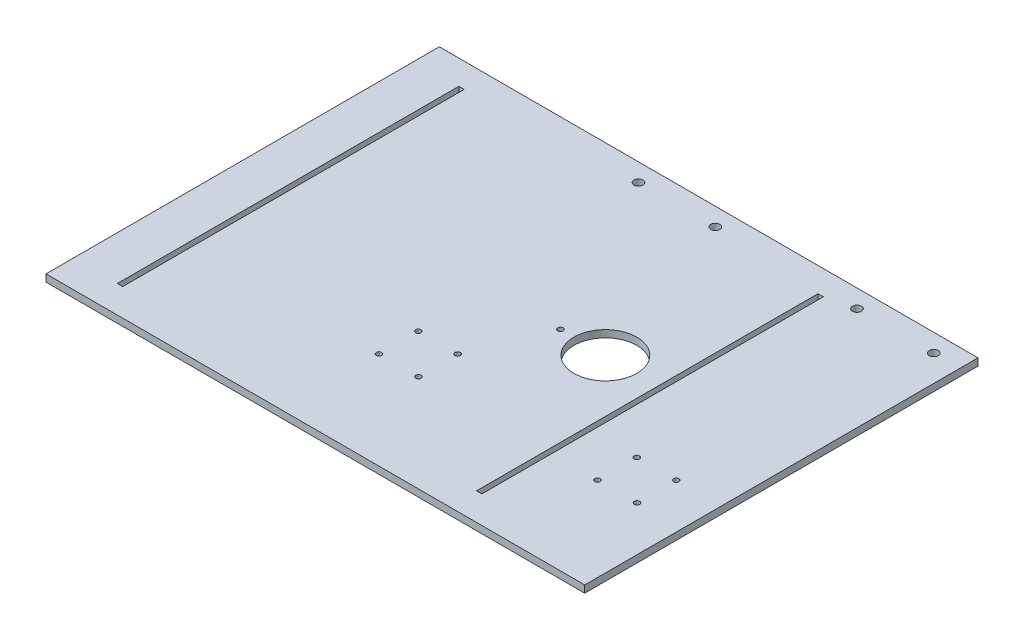
SolidWorks part; units mm, degrees
ref_plane "Front Plane" through (0, 0, 0) normal (0, 0, 1) x (1, 0, 0)
ref_plane "Top Plane" through (0, 0, 0) normal (0, 1, 0) x (1, 0, 0)
ref_plane "Right Plane" through (0, 0, 0) normal (1, 0, 0) x (0, 0, -1)
sketch "Sketch1" plane through (0, 0, 0) normal (0, 1, 0) x (1, 0, 0)
  line L0 (-125.5, 95.8859) -> (-125.5, -94.2851)
  line L1 (-150, -109.5) -> (150, -109.5)
  line L2 (-150, -109.5) -> (-150, 109.5)
  line L3 (-150, 109.5) -> (150, 109.5)
  line L4 (150, -109.5) -> (150, 109.5)
  line L5 (-150, -109.5) -> (150, 109.5) construction
  line L6 (-150, 109.5) -> (150, -109.5) construction
  line L7 (-125.5, -94.2851) -> (-122.5, -94.2851)
  line L8 (-122.5, -94.2851) -> (-122.5, 95.8859)
  line L9 (-122.5, 95.8859) -> (-125.5, 95.8859)
  line L10 (74.5, 95.8859) -> (74.5, -94.2851)
  line L11 (74.5, -94.2851) -> (77.5, -94.2851)
  line L12 (77.5, -94.2851) -> (77.5, 95.8859)
  line L13 (77.5, 95.8859) -> (74.5, 95.8859)
  point P0 (0, 0)
  dimension "D1" = 219
  dimension "D2" = 300
  dimension "D3" = 3
  dimension "D4" = 3
  dimension "D5" = 72.5
  dimension "D6" = 24.5
extrude "Boss-Extrude1" add sketch "Sketch1" along normal blind 4
sketch "Sketch2" plane through (0, 0, 0) normal (0, -1, 0) x (-1, 0, 0)
  line L0 (150, -109.5) -> (-150, -109.5) construction
  line L1 (-150, -109.5) -> (-150, 109.5) construction
  circle A0 centre (-45, 7) radius 17.5
  dimension "D3" = 35
  dimension "D1" = 116.5
  dimension "D2" = 105
extrude "Cut-Extrude2" cut sketch "Sketch2" against normal through all
sketch "Sketch3" plane through (0, 0, 0) normal (0, -1, 0) x (-1, 0, 0)
  line L0 (-150, -109.5) -> (-150, 109.5) construction
  line L1 (150, -109.5) -> (-150, -109.5) construction
  circle A0 centre (-125, -55.39) radius 1.5
  circle A1 centre (-125, -33.54) radius 1.5
  circle A2 centre (-103, -33.54) radius 1.5
  circle A3 centre (-103, -55.39) radius 1.5
  dimension "D1" = 3
  dimension "D6" = 22
  dimension "D9" = 21.85
  dimension "D2" = 25
  dimension "D3" = 25
  dimension "D4" = 54.11
  dimension "D5" = 54.11
  dimension "D7" = 22
  dimension "D8" = 21.85
extrude "Cut-Extrude3" cut sketch "Sketch3" against normal through all both and the other way through all
sketch "Sketch4" plane through (0, 0, 0) normal (0, -1, 0) x (-1, 0, 0)
  line L0 (-150, -109.5) -> (-150, 109.5) construction
  line L1 (150, -109.5) -> (-150, -109.5) construction
  circle A0 centre (-3.32, -55.39) radius 1.5
  circle A1 centre (-3.32, -33.54) radius 1.5
  circle A2 centre (18.68, -33.54) radius 1.5
  circle A3 centre (18.68, -55.39) radius 1.5
  dimension "D1" = 3
  dimension "D2" = 146.68
  dimension "D4" = 146.68
  dimension "D5" = 21.85
  dimension "D6" = 54.11
  dimension "D7" = 54.11
  dimension "D8" = 22
  dimension "D3" = 21.85
extrude "Cut-Extrude4" cut sketch "Sketch4" against normal through all both and the other way through all
sketch "Sketch5" plane through (0, 0, 0) normal (0, -1, 0) x (-1, 0, 0)
  line L0 (-150, 109.5) -> (150, 109.5) construction
  line L1 (-150, -109.5) -> (-150, 109.5) construction
  circle A0 centre (-135.39, 99.5) radius 2.5
  circle A1 centre (-92.61, 99.5) radius 2.5
  dimension "D1" = 5
  dimension "D2" = 10
  dimension "D3" = 10
  dimension "D4" = 42.78
  dimension "D5" = 14.61
extrude "Cut-Extrude5" cut sketch "Sketch5" against normal through all both and the other way through all
sketch "Sketch6" plane through (0, 0, 0) normal (0, -1, 0) x (1, 0, 0)
  line L0 (150, -109.5) -> (-150, -109.5) construction
  line L1 (150, 109.5) -> (150, -109.5) construction
  circle A0 centre (13.71, -99.5) radius 2.5
  circle A1 centre (-29.07, -99.5) radius 2.5
  dimension "D1" = 10
  dimension "D2" = 10
  dimension "D3" = 5
  dimension "D4" = 136.29
  dimension "D5" = 42.78
extrude "Cut-Extrude6" cut sketch "Sketch6" against normal through all both and the other way through all
sketch "Sketch7" plane through (0, 4, 0) normal (0, 1, 0) x (1, 0, 0)
  line L0 (150, -109.5) -> (150, 109.5) construction
  line L1 (-150, -109.5) -> (150, -109.5) construction
  circle A0 centre (20, 7) radius 1.5
  dimension "D1" = 3
  dimension "D2" = 130
  dimension "D3" = 116.5
extrude "Cut-Extrude7" cut sketch "Sketch7" against normal through all both and the other way through all
